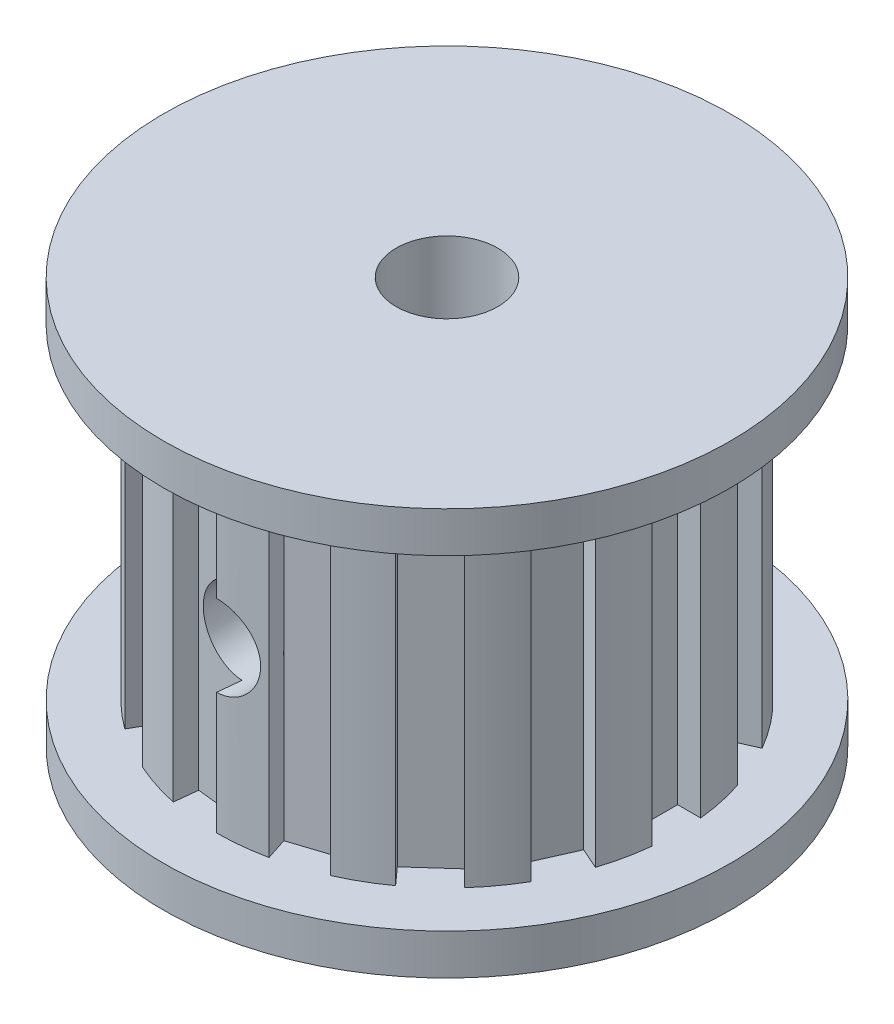
SolidWorks part; units mm, degrees
ref_plane "前视基准面" through (0, 0, 0) normal (0, 0, 1) x (1, 0, 0)
ref_plane "上视基准面" through (0, 0, 0) normal (0, 1, 0) x (1, 0, 0)
ref_plane "右视基准面" through (0, 0, 0) normal (1, 0, 0) x (0, 0, -1)
sketch "草图1" plane through (0, 0, 0) normal (0, 1, 0) x (1, 0, 0)
  circle A0 centre (0, 0) radius 11.35
  dimension "D1" = 22.7
extrude "凸台-拉伸1" add sketch "草图1" along normal mid plane 16 contours A0
sketch "草图2" plane through (0, 8, 0) normal (0, 1, 0) x (1, 0, 0)
  circle A0 centre (0, 0) radius 13.95
  dimension "D1" = 27.9
extrude "凸台-拉伸2" add sketch "草图2" along normal blind 2 contours A0
sketch "草图3" plane through (0, -8, 0) normal (0, -1, 0) x (1, 0, 0)
  circle A0 centre (0, 0) radius 13.95
  dimension "D1" = 27.9
extrude "凸台-拉伸3" add sketch "草图3" along normal blind 2 contours A0
sketch "草图4" plane through (0, 10, 0) normal (0, 1, 0) x (1, 0, 0)
  circle A0 centre (0, 0) radius 2.5
  dimension "D1" = 5
extrude "切除-拉伸1" cut sketch "草图4" against normal through all contours A0
sketch "草图5" plane through (0, 0, 0) normal (0, 0, 1) x (1, 0, 0)
  circle A0 centre (0, 0) radius 2
  dimension "D1" = 4
extrude "切除-拉伸2" cut sketch "草图5" along normal through all
sketch "草图6" plane through (0, 0, 0) normal (0, 0, 1) x (1, 0, 0)
  line L0 (-11.35, 8) -> (11.35, 8) construction
  line L1 (10.15, 8) -> (12.55, 8)
  line L2 (10.15, 8) -> (10.15, -8)
  line L3 (10.15, -8) -> (12.55, -8)
  line L4 (12.55, 8) -> (12.55, -8)
  line L5 (13.95, -8) -> (-13.95, -8) construction
  dimension "D1" = 2.4
  dimension "D2" = 10.15
extrude "切除-拉伸3" cut sketch "草图6" against normal mid plane 2.4 contours L4 L3 L2 L1
sketch "草图7" plane through (0, 0, 0) normal (0, 0, 1) x (1, 0, 0)
  line L0 (0, 10.6504) -> (0, -10.7338) construction
pattern_circular "阵列(圆周)1" count 15 over 360 about axis through (0, 0, 0) along (0, 1, 0) of "切除-拉伸3"
